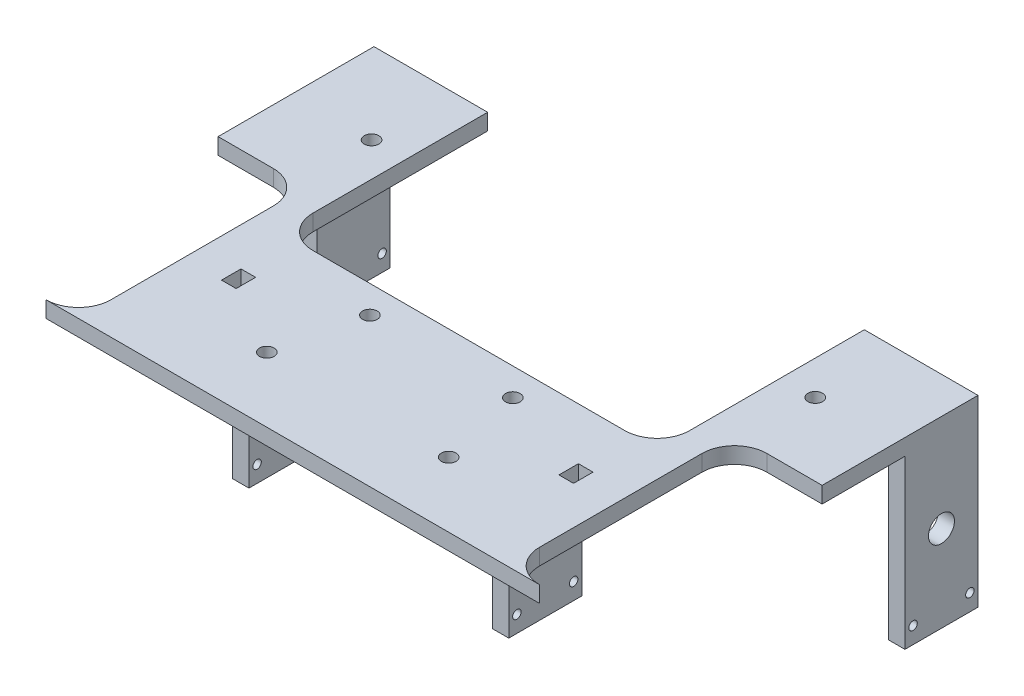
SolidWorks part; units mm, degrees
ref_plane "Front Plane" through (0, 0, 0) normal (0, 0, 1) x (1, 0, 0)
ref_plane "Top Plane" through (0, 0, 0) normal (0, 1, 0) x (1, 0, 0)
ref_plane "Right Plane" through (0, 0, 0) normal (1, 0, 0) x (0, 0, -1)
sketch "Sketch1" plane through (0, 0, 0) normal (0, 1, 0) x (1, 0, 0)
  line L0 (0, 0) -> (0, -300)
  line L1 (0, -300) -> (186, -300)
  line L2 (186, -300) -> (186, 0)
  line L3 (186, 0) -> (176, 0)
  line L4 (176, 0) -> (151, 0)
  line L5 (151, 0) -> (151, -56.1159)
  line L6 (151, -56.1159) -> (35, -56.1159)
  line L7 (35, -56.1159) -> (35, 0)
  line L8 (35, 0) -> (10, 0)
  line L9 (10, 0) -> (0, 0)
  line L10 (93, -300) -> (93, -56.1159) construction
  point P9 (93, -56.1159)
  dimension "D1" = 300
  dimension "D2" = 10
  dimension "D3" = 186
  dimension "D5" = 10
  dimension "D6" = 35
extrude "Boss-Extrude1" add sketch "Sketch1" along normal blind 5
sketch "Sketch2" plane through (0, 0, 0) normal (0, -1, 0) x (1, 0, 0)
  line L1 (50.5, 94) -> (55.5, 94)
  line L2 (50.5, 94) -> (50.5, 71.5)
  line L3 (50.5, 71.5) -> (55.5, 71.5)
  line L4 (55.5, 94) -> (55.5, 71.5)
  line L6 (135.5, 94) -> (130.5, 94)
  line L7 (135.5, 94) -> (135.5, 71.5)
  line L8 (135.5, 71.5) -> (130.5, 71.5)
  line L9 (130.5, 94) -> (130.5, 71.5)
  line L10 (0, 300) -> (186, 300) construction
  line L11 (186, 300) -> (186, 0) construction
  line L12 (0, 0) -> (0, 300) construction
  dimension "D1" = 5
  dimension "D2" = 22.5
  dimension "D3" = 5
  dimension "D4" = 206
  dimension "D5" = 22.5
  dimension "D6" = 50.5
  dimension "D7" = 50.5
extrude "Boss-Extrude2" add sketch "Sketch2" along normal blind 38
sketch "Sketch5" plane through (0, 0, 0) normal (0, -1, 0) x (1, 0, 0)
  line L0 (186, 300) -> (186, 0) construction
  line L1 (186, 295) -> (161, 295)
  line L2 (186, 295) -> (186, 300)
  line L3 (186, 300) -> (161, 300)
  line L4 (161, 295) -> (161, 300)
  line L5 (0, 300) -> (186, 300) construction
  line L6 (186, 240) -> (161, 240)
  line L7 (186, 240) -> (186, 245)
  line L8 (186, 245) -> (161, 245)
  line L9 (161, 240) -> (161, 245)
  line L10 (186, 185) -> (161, 185)
  line L11 (186, 185) -> (186, 190)
  line L12 (186, 190) -> (161, 190)
  line L13 (161, 185) -> (161, 190)
  line L14 (186, 130) -> (161, 130)
  line L15 (186, 130) -> (186, 135)
  line L16 (186, 135) -> (161, 135)
  line L17 (161, 130) -> (161, 135)
  dimension "D1" = 5
  dimension "D2" = 5
  dimension "D3" = 5
  dimension "D4" = 5
  dimension "D5" = 50
  dimension "D6" = 50
  dimension "D7" = 50
  dimension "D8" = 25
extrude "Boss-Extrude3" add sketch "Sketch5" along normal blind 30
fillet "Fillet3" radius 5 4 edges at (173.5, 0, 130) (173.5, 0, 185) (173.5, 0, 240) (173.5, 0, 295)
sketch "Sketch6" plane through (0, 0, 300) normal (0, 0, 1) x (1, 0, 0)
  line L0 (186, -30) -> (161, -30) construction
  line L1 (186, 5) -> (186, -30) construction
  circle A0 centre (178, -24) radius 3
  dimension "D1" = 6
  dimension "D2" = 6
  dimension "D3" = 8
extrude "Cut-Extrude4" cut sketch "Sketch6" against normal blind 172
sketch "Sketch7" plane through (0, 0, 0) normal (0, -1, 0) x (1, 0, 0)
  line L0 (0, 0) -> (0, 300) construction
  line L1 (0, 22.5) -> (5, 22.5)
  line L2 (0, 22.5) -> (0, 0)
  line L3 (0, 0) -> (5, 0)
  line L4 (5, 22.5) -> (5, 0)
  line L5 (186, 125) -> (186, 0) construction
  line L6 (186, 22.5) -> (181, 22.5)
  line L7 (186, 22.5) -> (186, 0)
  line L8 (186, 0) -> (181, 0)
  line L9 (181, 22.5) -> (181, 0)
  line L10 (186, 0) -> (151, 0) construction
  dimension "D1" = 5
  dimension "D2" = 5
  dimension "D3" = 22.5
  dimension "D4" = 22.5
extrude "Boss-Extrude4" add sketch "Sketch7" along normal blind 51.5
sketch "Sketch3" plane through (186, 0, 0) normal (1, 0, 0) x (0, 0, -1)
  line L4 (-71.5, 0) -> (-94, 0)
  line L5 (-71.5, -38) -> (-71.5, 0)
  line L6 (-94, -38) -> (-71.5, -38)
  line L7 (-94, 0) -> (-94, -38)
  line L9 (-71.5, -38) -> (-71.5, 0)
  line L10 (-94, -38) -> (-71.5, -38)
  line L11 (-94, 0) -> (-94, -38)
  line L13 (-71.5, 0) -> (-94, 0)
  circle A0 centre (-74, -32.9) radius 1.3 construction
  circle A1 centre (-91.5, -32.9) radius 1.3 construction
  circle A2 centre (-74, -32.9) radius 1.3
  circle A3 centre (-91.5, -32.9) radius 1.3
  circle A4 centre (-20, -46.4) radius 1.3 construction
  circle A5 centre (-2.5, -46.4) radius 1.3 construction
  circle A6 centre (-20, -46.4) radius 1.3
  circle A7 centre (-2.5, -46.4) radius 1.3
  dimension "D1" = 0
extrude "Cut-Extrude2" cut sketch "Sketch3" against normal through all contours A3 | A2 | A6 | A7
sketch "Sketch9" plane through (0, 0, 0) normal (0, -1, 0) x (1, 0, 0)
  line L0 (35, 0) -> (5, 0) construction
  line L1 (35, 0) -> (151, 0)
  line L2 (35, 0) -> (35, 63.7796)
  line L3 (35, 63.7796) -> (151, 63.7796)
  line L4 (151, 0) -> (151, 63.7796)
  line L5 (35, 56.1159) -> (35, 0) construction
  line L6 (151, 0) -> (151, 56.1159) construction
extrude "Cut-Extrude6" cut sketch "Sketch9" against normal blind 10
sketch "Sketch10" plane through (0, -30, 0) normal (0, -1, 0) x (1, 0, 0)
  line L1 (186, 295) -> (161, 295)
  line L2 (186, 295) -> (186, 300)
  line L3 (186, 300) -> (161, 300)
  line L4 (161, 295) -> (161, 300)
  line L5 (161, 130) -> (186, 130)
  line L6 (161, 130) -> (161, 135)
  line L7 (161, 135) -> (186, 135)
  line L8 (186, 130) -> (186, 135)
extrude "Boss-Extrude5" add sketch "Sketch10" along normal blind 70
sketch "Sketch11" plane through (186, 0, 0) normal (1, 0, 0) x (0, 0, -1)
  line L0 (-300, -100) -> (-304.9019, -134.6439)
  line L1 (-304.9019, -134.6439) -> (-300, -135.3374)
  line L2 (-300, -135.3374) -> (-295, -100)
  line L3 (-300, -100) -> (-295, -100)
extrude "Boss-Extrude6" add sketch "Sketch11" against normal blind 25
sketch "Sketch12" plane through (0, -100, 0) normal (0, -1, 0) x (1, 0, 0)
  line L1 (161, 130) -> (186, 130)
  line L2 (161, 130) -> (161, 135)
  line L3 (161, 135) -> (186, 135)
  line L4 (186, 130) -> (186, 135)
extrude "Boss-Extrude7" add sketch "Sketch12" along normal blind 19.72
sketch "Sketch13" plane through (0, 0, 130) normal (0, 0, -1) x (-1, 0, 0)
  line L0 (-186, -115.3141) -> (-186, -119.72)
  line L1 (-186, -119.72) -> (-186, -5) construction
  line L2 (-186, -119.72) -> (-161, -123.1352)
  line L3 (-161, -123.1352) -> (-161, -115.3141)
  line L4 (-161, -115.3141) -> (-186, -115.3141)
  line L5 (-161, -119.72) -> (-161, -5) construction
  line L8 (-88.5025, -135.5912) -> (-182.3051, -122.777) construction
extrude "Boss-Extrude8" add sketch "Sketch13" along normal blind 15 and the other way blind 4
sketch "Sketch14" plane through (19.4625, -142.4702, 0) normal (0.1354, -0.9908, 0) x (0.9908, 0.1354, 0)
  line L0 (186.3576, 115) -> (168.0843, 132.0374)
  line L1 (168.0843, 115) -> (142.8521, 115) construction
  line L2 (168.0843, 115) -> (168.0843, 134) construction
  line L3 (168.0843, 132.0374) -> (198.0152, 130.431)
  line L4 (198.0152, 130.431) -> (197.5151, 111.3666)
  line L5 (197.5151, 111.3666) -> (186.3576, 109.6075)
  line L6 (186.3576, 109.6075) -> (186.3576, 115)
extrude "Cut-Extrude7" cut sketch "Sketch14" against normal blind 15
sketch "Sketch15" plane through (0, 39.652, 280.2402) normal (0, 0.1401, 0.9901) x (1, 0, 0)
  line L1 (161, -141.043) -> (161, -176.032) construction
  line L2 (186, -141.043) -> (161, -141.043) construction
  line L3 (186, -141.043) -> (186, -176.032) construction
  line L4 (161, -176.032) -> (186, -176.032) construction
  circle A0 centre (178, -168.032) radius 2.25
  circle A1 centre (169, -149.043) radius 2.25
  dimension "D1" = 4.5
  dimension "D2" = 4.5
  dimension "D3" = 8
  dimension "D4" = 8
  dimension "D5" = 8
  dimension "D6" = 8
extrude "Cut-Extrude8" cut sketch "Sketch15" against normal blind 20
sketch "Sketch16" plane through (0, 0, 0) normal (0, -1, 0) x (1, 0, 0)
  line L1 (166, 272) -> (172, 272)
  line L2 (166, 272) -> (166, 275)
  line L3 (166, 275) -> (172, 275)
  line L4 (172, 272) -> (172, 275)
  line L5 (143.4, 272) -> (137.4, 272)
  line L6 (143.4, 272) -> (143.4, 275)
  line L7 (143.4, 275) -> (137.4, 275)
  line L8 (137.4, 272) -> (137.4, 275)
  line L9 (166, 217) -> (172, 217)
  line L10 (166, 217) -> (166, 220)
  line L11 (166, 220) -> (172, 220)
  line L12 (172, 217) -> (172, 220)
  line L13 (166, 162) -> (172, 162)
  line L14 (166, 162) -> (166, 165)
  line L15 (166, 165) -> (172, 165)
  line L16 (172, 162) -> (172, 165)
  line L17 (137.4, 217) -> (143.4, 217)
  line L18 (137.4, 217) -> (137.4, 220)
  line L19 (137.4, 220) -> (143.4, 220)
  line L20 (143.4, 217) -> (143.4, 220)
  line L21 (137.4, 162) -> (143.4, 162)
  line L22 (137.4, 162) -> (137.4, 165)
  line L23 (137.4, 165) -> (143.4, 165)
  line L24 (143.4, 162) -> (143.4, 165)
  line L25 (186, 180) -> (186, 135) construction
  line L28 (161, 295) -> (186, 295) construction
  line L29 (161, 240) -> (186, 240) construction
  line L30 (161, 185) -> (186, 185) construction
  dimension "D1" = 3
  dimension "D2" = 3
  dimension "D3" = 3
  dimension "D4" = 3
  dimension "D5" = 3
  dimension "D6" = 3
  dimension "D7" = 20
  dimension "D8" = 22.6
  dimension "D9" = 6
  dimension "D10" = 6
  dimension "D11" = 23
  dimension "D12" = 23
  dimension "D13" = 23
extrude "Boss-Extrude9" add sketch "Sketch16" along normal blind 12.4
sketch "Sketch17" plane through (0, 0, 162) normal (0, 0, -1) x (-1, 0, 0)
  arc A0 (-169.75, -6.8) -> (-169.75, -5.6) centre (-168.95, -6.2) ccw construction
  arc A1 (-169.75, -6.8) -> (-169.75, -5.6) centre (-168.95, -6.2) ccw
  circle A2 centre (-168.95, -6.2) radius 1
  circle A3 centre (-140.45, -6.2) radius 1
extrude "Cut-Extrude9" cut sketch "Sketch17" against normal through all contours A1 A2 | A3
sketch "Sketch27" plane through (19.4625, -142.4702, 0) normal (0.1354, -0.9908, 0) x (0.9908, 0.1354, 0)
  line L1 (142.8521, 115) -> (168.0843, 115)
  line L2 (142.8521, 115) -> (142.8521, 134)
  line L3 (142.8521, 134) -> (168.0843, 134)
  line L4 (168.0843, 115) -> (168.0843, 134)
extrude "Boss-Extrude11" add sketch "Sketch27" along normal blind 3
fillet "Fillet4" radius 5 6 edges at (140.4, 0, 275) (169, 0, 275) (140.4, 0, 220) (169, 0, 220) (140.4, 0, 165) (169, 0, 165)
sketch "Sketch18" plane through (0, -115.3141, 0) normal (0, 1, 0) x (1, 0, 0)
  circle A0 centre (174.8857, -120.9947) radius 2.25
  dimension "D1" = 4.5
extrude "Cut-Extrude10" cut sketch "Sketch18" against normal through all
sketch "Sketch19" plane through (0, 0, 0) normal (0, -1, 0) x (1, 0, 0)
  line L0 (42.3, 80.75) -> (39.8, 80.75) construction
  line L1 (39.8, 84.75) -> (39.8, 80.75) construction
  line L2 (42.3, 84.75) -> (42.3, 80.75) construction
  line L3 (39.8, 84.75) -> (42.3, 84.75) construction
  line L4 (42.3, 80.75) -> (39.8, 80.75) construction
  line L5 (39.8, 84.75) -> (39.8, 80.75) construction
  line L6 (42.3, 84.75) -> (42.3, 80.75) construction
  line L7 (39.8, 84.75) -> (42.3, 84.75) construction
  line L8 (143.7, 80.75) -> (143.7, 84.75) construction
  line L9 (143.7, 84.75) -> (146.2, 84.75) construction
  line L10 (146.2, 80.75) -> (146.2, 84.75) construction
  line L11 (146.2, 80.75) -> (143.7, 80.75) construction
  line L12 (143.7, 80.75) -> (143.7, 84.75) construction
  line L13 (143.7, 84.75) -> (146.2, 84.75) construction
  line L14 (146.2, 80.75) -> (146.2, 84.75) construction
  line L15 (146.2, 80.75) -> (143.7, 80.75) construction
  line L16 (43.3, 79.75) -> (38.8, 79.75)
  line L17 (38.8, 85.75) -> (38.8, 79.75)
  line L18 (38.8, 85.75) -> (43.3, 85.75)
  line L19 (43.3, 85.75) -> (43.3, 79.75)
  line L20 (142.7, 79.75) -> (142.7, 85.75)
  line L21 (142.7, 85.75) -> (147.2, 85.75)
  line L22 (147.2, 79.75) -> (147.2, 85.75)
  line L23 (147.2, 79.75) -> (142.7, 79.75)
  line L31 (151, 0) -> (181, 0)
  line L32 (181, 0) -> (181, 22.5)
  line L34 (186, 22.5) -> (186, 125)
  line L35 (186, 125) -> (161, 125)
  line L36 (161, 125) -> (161, 135)
  line L37 (161, 135) -> (186, 135)
  line L38 (186, 135) -> (186, 180)
  line L39 (186, 180) -> (161, 180)
  line L40 (161, 180) -> (161, 190)
  line L41 (161, 190) -> (186, 190)
  line L42 (186, 190) -> (186, 235)
  line L43 (186, 235) -> (161, 235)
  line L44 (161, 235) -> (161, 245)
  line L45 (161, 245) -> (186, 245)
  line L46 (186, 245) -> (186, 290)
  line L47 (186, 290) -> (161, 290)
  line L48 (161, 290) -> (161, 300)
  line L49 (161, 300) -> (0, 300)
  line L50 (0, 300) -> (0, 22.5)
  line L51 (0, 22.5) -> (5, 22.5)
  line L52 (5, 22.5) -> (5, 0)
  line L53 (5, 0) -> (35, 0)
  line L56 (151, 63.7796) -> (151, 0)
  line L57 (151, 63.7796) -> (151, 0)
  line L58 (35, 0) -> (35, 63.7796)
  line L61 (151, 0) -> (181, 0)
  line L64 (186, 22.5) -> (186, 125)
  line L65 (186, 125) -> (161, 125)
  line L66 (161, 125) -> (161, 135)
  line L67 (161, 135) -> (186, 135)
  line L68 (186, 135) -> (186, 180)
  line L69 (186, 180) -> (161, 180)
  line L70 (161, 180) -> (161, 190)
  line L71 (161, 190) -> (186, 190)
  line L72 (186, 190) -> (186, 235)
  line L73 (186, 235) -> (161, 235)
  line L74 (161, 235) -> (161, 245)
  line L75 (161, 245) -> (186, 245)
  line L76 (186, 245) -> (186, 290)
  line L77 (186, 290) -> (161, 290)
  line L78 (161, 290) -> (161, 300)
  line L79 (161, 300) -> (0, 300)
  line L80 (0, 300) -> (0, 22.5)
  line L81 (0, 22.5) -> (5, 22.5)
  line L82 (5, 22.5) -> (5, 0)
  line L83 (5, 0) -> (35, 0)
  line L106 (35, 0) -> (35, 63.7796)
  line L107 (35, 63.7796) -> (151, 63.7796)
  line L108 (35, 63.7796) -> (151, 63.7796)
  line L116 (181, 22.5) -> (186, 22.5)
  line L122 (181, 22.5) -> (186, 22.5)
  line L124 (181, 0) -> (181, 22.5)
  dimension "D1" = 0
  dimension "D2" = 1
  dimension "D3" = 1
extrude "Cut-Extrude12" cut sketch "Sketch19" against normal through all contours L23 L22 L21 L20 | L19 L18 L17 L16
fillet "Fillet6" radius 10 2 edges at (151, 2.5, 63.7796) (35, 2.5, 63.7796)
sketch "Sketch21" plane through (0, 0, 0) normal (0, -1, 0) x (1, 0, 0)
  line L0 (0, 22.5) -> (0, 300) construction
  line L1 (0, 48) -> (27, 48)
  line L2 (0, 48) -> (0, 118)
  line L3 (0, 118) -> (27, 118)
  line L4 (27, 48) -> (27, 118)
  line L5 (186, 125) -> (186, 22.5) construction
  line L6 (186, 48) -> (159, 48)
  line L7 (186, 48) -> (186, 118)
  line L8 (186, 118) -> (159, 118)
  line L9 (159, 48) -> (159, 118)
  line L10 (0, 300) -> (161, 300) construction
  dimension "D1" = 70
  dimension "D2" = 182
  dimension "D3" = 70
  dimension "D4" = 182
  dimension "D5" = 27
  dimension "D6" = 27
extrude "Cut-Extrude14" cut sketch "Sketch21" against normal through all
fillet "Fillet7" radius 10 4 edges at (27, 2.5, 118) (27, 2.5, 48) (159, 2.5, 48) (159, 2.5, 118)
sketch "Sketch22" plane through (0, 0, 0) normal (0, -1, 0) x (1, 0, 0)
  line L34 (17, 48) -> (0, 48)
  line L35 (0, 48) -> (0, 22.5)
  line L36 (0, 22.5) -> (5, 22.5)
  line L37 (5, 22.5) -> (5, 0)
  line L38 (5, 0) -> (35, 0)
  line L39 (35, 0) -> (35, 53.7796)
  line L40 (45, 63.7796) -> (141, 63.7796)
  line L41 (151, 53.7796) -> (151, 0)
  line L42 (151, 0) -> (181, 0)
  line L43 (181, 0) -> (181, 22.5)
  line L44 (181, 22.5) -> (186, 22.5)
  line L45 (186, 22.5) -> (186, 48)
  line L46 (186, 48) -> (169, 48)
  line L47 (159, 58) -> (159, 108)
  line L48 (169, 118) -> (186, 118)
  line L49 (186, 118) -> (186, 125)
  line L50 (186, 125) -> (161, 125)
  line L51 (161, 125) -> (161, 135)
  line L52 (161, 135) -> (186, 135)
  line L53 (186, 135) -> (186, 180)
  line L54 (186, 180) -> (161, 180)
  line L55 (161, 180) -> (161, 190)
  line L56 (161, 190) -> (186, 190)
  line L57 (186, 190) -> (186, 235)
  line L58 (186, 235) -> (161, 235)
  line L59 (161, 235) -> (161, 245)
  line L60 (161, 245) -> (186, 245)
  line L61 (186, 245) -> (186, 290)
  line L62 (186, 290) -> (161, 290)
  line L63 (161, 290) -> (161, 300)
  line L64 (161, 300) -> (0, 300)
  line L65 (0, 300) -> (0, 118)
  line L66 (0, 118) -> (17, 118)
  line L67 (27, 108) -> (27, 58)
  line L68 (17, 48) -> (0, 48)
  line L69 (0, 48) -> (0, 22.5)
  line L70 (0, 22.5) -> (5, 22.5)
  line L71 (5, 22.5) -> (5, 0)
  line L72 (5, 0) -> (35, 0)
  line L73 (35, 0) -> (35, 53.7796)
  line L74 (45, 63.7796) -> (141, 63.7796)
  line L75 (151, 53.7796) -> (151, 0)
  line L76 (151, 0) -> (181, 0)
  line L77 (181, 0) -> (181, 22.5)
  line L78 (181, 22.5) -> (186, 22.5)
  line L79 (186, 22.5) -> (186, 48)
  line L80 (186, 48) -> (169, 48)
  line L81 (159, 58) -> (159, 108)
  line L82 (169, 118) -> (186, 118)
  line L83 (186, 118) -> (186, 125)
  line L84 (186, 125) -> (161, 125)
  line L85 (161, 125) -> (161, 135)
  line L86 (161, 135) -> (186, 135)
  line L87 (186, 135) -> (186, 180)
  line L88 (186, 180) -> (161, 180)
  line L89 (161, 180) -> (161, 190)
  line L90 (161, 190) -> (186, 190)
  line L91 (186, 190) -> (186, 235)
  line L92 (186, 235) -> (161, 235)
  line L93 (161, 235) -> (161, 245)
  line L94 (161, 245) -> (186, 245)
  line L95 (186, 245) -> (186, 290)
  line L96 (186, 290) -> (161, 290)
  line L97 (161, 290) -> (161, 300)
  line L98 (161, 300) -> (0, 300)
  line L99 (0, 300) -> (0, 118)
  line L100 (0, 118) -> (17, 118)
  line L101 (27, 108) -> (27, 58)
  circle A4 centre (24.5, 25.25) radius 2.25 construction
  circle A5 centre (24.5, 25.25) radius 2.25
  arc A6 (45, 63.7796) -> (35, 53.7796) centre (45, 53.7796) ccw
  arc A7 (151, 53.7796) -> (141, 63.7796) centre (141, 53.7796) ccw
  arc A8 (159, 58) -> (169, 48) centre (169, 58) ccw
  arc A9 (169, 118) -> (159, 108) centre (169, 108) ccw
  arc A10 (27, 108) -> (17, 118) centre (17, 108) ccw
  arc A11 (17, 48) -> (27, 58) centre (17, 58) ccw
  arc A12 (45, 63.7796) -> (35, 53.7796) centre (45, 53.7796) ccw
  arc A13 (151, 53.7796) -> (141, 63.7796) centre (141, 53.7796) ccw
  arc A14 (159, 58) -> (169, 48) centre (169, 58) ccw
  arc A15 (169, 118) -> (159, 108) centre (169, 108) ccw
  arc A16 (27, 108) -> (17, 118) centre (17, 108) ccw
  arc A17 (17, 48) -> (27, 58) centre (17, 58) ccw
  circle A18 centre (161.5, 25.6175) radius 2.25 construction
  circle A19 centre (161.5, 25.6175) radius 2.25
  circle A20 centre (115, 72.25) radius 2.25 construction
  circle A21 centre (115, 72.25) radius 2.25
  circle A22 centre (71, 72.25) radius 2.25 construction
  circle A23 centre (71, 72.25) radius 2.25
  dimension "D1" = 0
extrude "Cut-Extrude16" cut sketch "Sketch22" against normal blind 10
sketch "Sketch23" plane through (0, 0, 135) normal (0, 0, 1) x (1, 0, 0)
  line L1 (178.1063, -118.4368) -> (161.0628, -118.4368)
  line L2 (178.1063, -118.4368) -> (178.1063, -123.5756)
  line L3 (178.1063, -123.5756) -> (161.0628, -123.5756)
  line L4 (161.0628, -118.4368) -> (161.0628, -123.5756)
extrude "Boss-Extrude10" add sketch "Sketch23" along normal blind 7
sketch "Sketch24" plane through (161.0628, 0, 0) normal (-1, 0, 0) x (0, 0, 1)
  line L0 (295, -100) -> (133.6076, -122.8359) construction
  line L1 (142, -121.6484) -> (135, -122.6389)
  line L2 (135, -119.72) -> (135, -123.5756) construction
  line L3 (142, -118.4368) -> (142, -123.5756) construction
  line L4 (142, -121.6484) -> (142, -124.3381)
  line L5 (142, -124.3381) -> (134.715, -124.3381)
  line L6 (134.715, -124.3381) -> (135, -122.6389)
extrude "Cut-Extrude17" cut sketch "Sketch24" against normal up to next
sketch "Sketch25" plane through (0, -118.4368, 0) normal (0, 1, 0) x (1, 0, 0)
  circle A0 centre (174.7191, -138.0894) radius 2.25
  dimension "D1" = 4.5
extrude "Cut-Extrude18" cut sketch "Sketch25" against normal up to next
sketch "Sketch28" plane through (0, 5, 0) normal (0, 1, 0) x (1, 0, 0)
  line L0 (0, -300) -> (186, -300) construction
  circle A0 centre (93, -260) radius 2.25
  point P4 (93, -300)
  dimension "D1" = 4.5
  dimension "D2" = 40
extrude "Cut-Extrude19" cut sketch "Sketch28" against normal through all
sketch "Sketch30" plane through (0, 5, 0) normal (0, 1, 0) x (1, 0, 0)
  line L0 (186, -118) -> (169, -118) construction
  line L1 (-59.5189, -331.927) -> (379.4222, -331.927)
  line L2 (-59.5189, -331.927) -> (-59.5189, -118)
  line L3 (-59.5189, -118) -> (379.4222, -118)
  line L4 (379.4222, -331.927) -> (379.4222, -118)
extrude "Cut-Extrude22" cut sketch "Sketch30" against normal through all
sketch "Sketch31" plane through (0, 0, 115) normal (0, 0, -1) x (-1, 0, 0)
  line L1 (-129.7503, -141.3628) -> (-212.8844, -141.3628)
  line L2 (-129.7503, -141.3628) -> (-129.7503, -112.7031)
  line L3 (-129.7503, -112.7031) -> (-212.8844, -112.7031)
  line L4 (-212.8844, -141.3628) -> (-212.8844, -112.7031)
extrude "Cut-Extrude23" cut sketch "Sketch31" against normal through all
sketch "Sketch32" plane through (0, 0, 0) normal (0, -1, 0) x (1, 0, 0)
  line L0 (169, 118) -> (17, 118) construction
  line L1 (186, 48) -> (186, 22.5) construction
  line L2 (0, 22.5) -> (0, 48) construction
  circle A0 centre (121, 98) radius 2.25
  circle A1 centre (65, 98) radius 2.25
  dimension "D1" = 4.5
  dimension "D2" = 4.5
  dimension "D3" = 20
  dimension "D4" = 20
  dimension "D5" = 65
  dimension "D6" = 65
extrude "Cut-Extrude24" cut sketch "Sketch32" against normal through all
sketch "Sketch33" plane through (55.5, 0, 0) normal (1, 0, 0) x (0, 0, -1)
  line L4 (-71.5, -38) -> (-71.5, 0)
  line L5 (-71.5, 0) -> (-94, 0)
  line L6 (-94, 0) -> (-94, -38)
  line L7 (-94, -38) -> (-71.5, -38)
  line L8 (-71.5, -38) -> (-71.5, 0)
  line L10 (-94, 0) -> (-94, -38)
  line L11 (-94, -38) -> (-71.5, -38)
  line L12 (-71.5, 0) -> (-94, 0)
  circle A0 centre (-82.75, -11.4) radius 2.675 construction
  circle A1 centre (-82.75, -11.4) radius 2.675 construction
  circle A2 centre (-82.75, -11.4) radius 4
  dimension "D2" = 8
  dimension "D1" = 0
extrude "Cut-Extrude26" cut sketch "Sketch33" against normal blind 10 and the other way blind 110 contours A2
sketch "Sketch34" plane through (186, 0, 0) normal (1, 0, 0) x (0, 0, -1)
  line L6 (0, 5) -> (-48, 5)
  line L7 (-48, 5) -> (-48, 0)
  line L8 (-48, 0) -> (-22.5, 0)
  line L9 (-22.5, 0) -> (-22.5, -51.5)
  line L10 (-22.5, -51.5) -> (0, -51.5)
  line L11 (0, -51.5) -> (0, 5)
  line L12 (0, 5) -> (-48, 5)
  line L13 (-48, 5) -> (-48, 0)
  line L14 (-48, 0) -> (-22.5, 0)
  line L15 (-22.5, 0) -> (-22.5, -51.5)
  line L16 (-22.5, -51.5) -> (0, -51.5)
  line L17 (0, -51.5) -> (0, 5)
  circle A0 centre (-11.25, -24.9) radius 2.675 construction
  circle A1 centre (-11.25, -24.9) radius 2.675 construction
  circle A2 centre (-11.25, -24.9) radius 4
  dimension "D2" = 8
  dimension "D1" = 0
extrude "Cut-Extrude27" cut sketch "Sketch34" against normal through all contours A2
